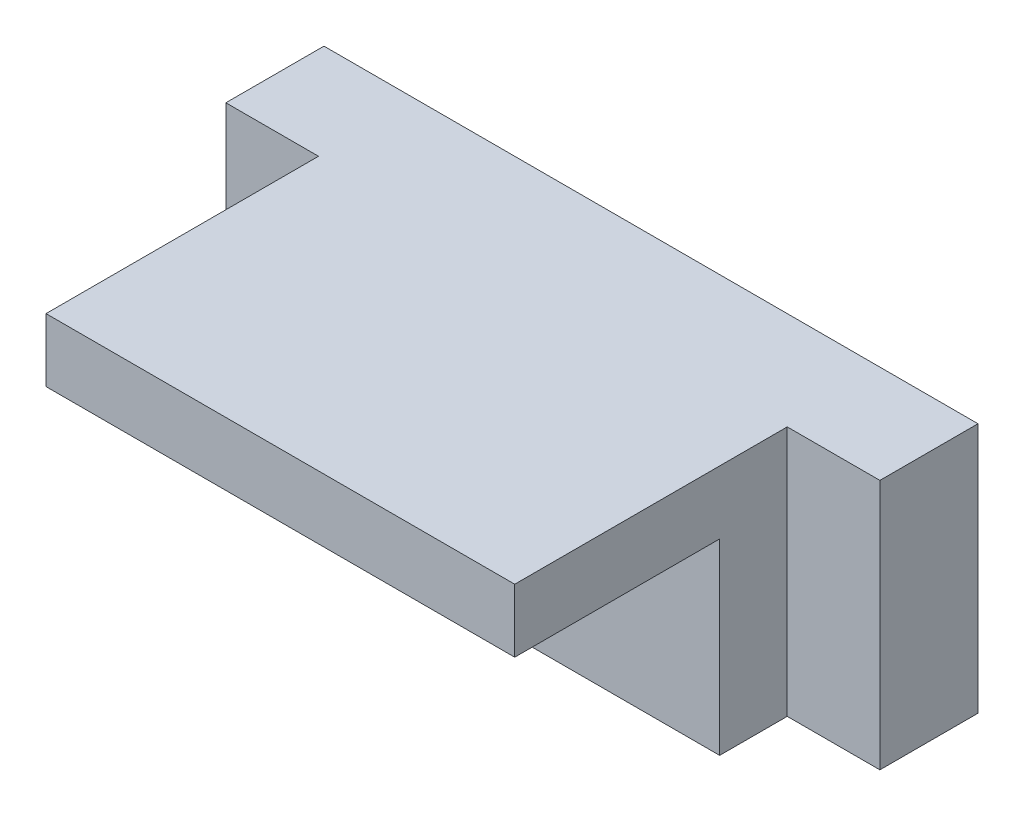
SolidWorks part; units mm, degrees
material "Свинец без примесей"
ref_plane "Front" through (0, 0, 0) normal (0, 0, 1) x (1, 0, 0)
ref_plane "Top" through (0, 0, 0) normal (0, 1, 0) x (1, 0, 0)
ref_plane "Right" through (0, 0, 0) normal (1, 0, 0) x (0, 0, -1)
sketch "Эскиз1" plane through (0, 0, 0) normal (0, 1, 0) x (1, 0, 0)
  line L0 (0, 0) -> (0, 47.3594) construction
  line L1 (-21.5, 0) -> (21.5, 0)
  line L2 (21.5, 0) -> (21.5, 25)
  line L3 (21.5, 25) -> (30, 25)
  line L4 (30, 25) -> (30, 34)
  line L5 (30, 34) -> (-30, 34)
  line L6 (-30, 25) -> (-30, 34)
  line L7 (-21.5, 25) -> (-30, 25)
  line L8 (-21.5, 0) -> (-21.5, 25)
  point P9 (0, 34)
  dimension "D1" = 43
  dimension "D2" = 25
  dimension "D3" = 60
  dimension "D4" = 34
extrude "Бобышка-Вытянуть1" add sketch "Эскиз1" along normal blind 23
sketch "Эскиз2" plane through (21.5, 0, 0) normal (1, 0, 0) x (0, 0, -1)
  line L0 (25, 23) -> (25, 0) construction
  line L1 (0, 0) -> (18.8, 0)
  line L2 (0, 0) -> (0, 17.2)
  line L3 (0, 17.2) -> (18.8, 17.2)
  line L4 (18.8, 0) -> (18.8, 17.2)
  line L5 (0, 23) -> (25, 23) construction
  dimension "D1" = 6.2
  dimension "D2" = 5.8
extrude "Вырез-Вытянуть1" cut sketch "Эскиз2" against normal blind 51
fillet "Скругление1" [suppressed] radius 1
